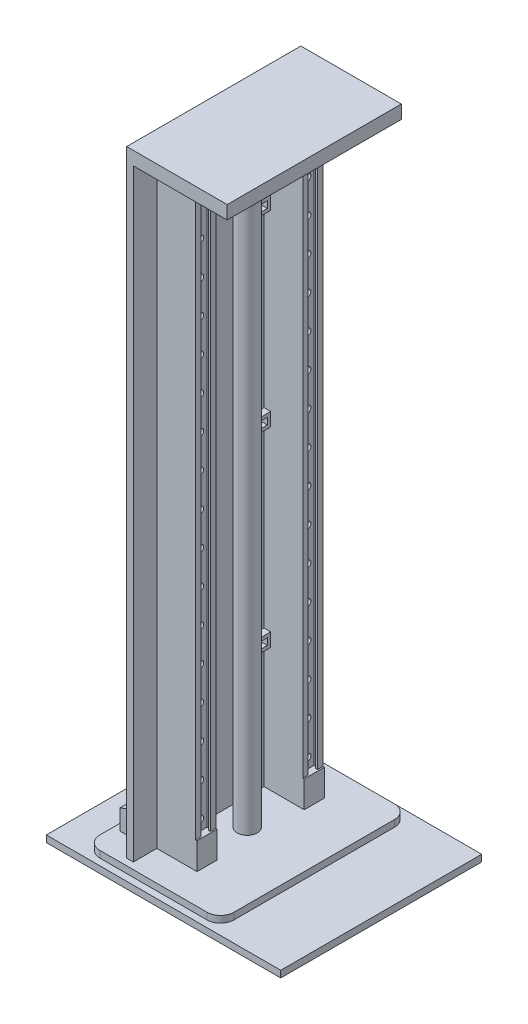
SolidWorks part; units mm, degrees
ref_plane "前视基准面" through (0, 0, 0) normal (0, 0, 1) x (1, 0, 0)
ref_plane "上视基准面" through (0, 0, 0) normal (0, 1, 0) x (1, 0, 0)
ref_plane "右视基准面" through (0, 0, 0) normal (1, 0, 0) x (0, 0, -1)
sketch "草图1" plane through (0, 0, 0) normal (0, 1, 0) x (1, 0, 0)
  line L1 (-150, 50) -> (-150, 150)
  line L2 (-150, 150) -> (200, 150)
  line L3 (200, 150) -> (200, -150)
  line L4 (200, -150) -> (-150, -150)
  line L5 (-150, -150) -> (-150, 50)
  dimension "D1" = 200
  dimension "D2" = 150
  dimension "D3" = 150
extrude "凸台-拉伸1" add sketch "草图1" along normal blind 10
sketch "草图2" plane through (0, 10, 0) normal (0, 1, 0) x (1, 0, 0)
  line L1 (-100, -20) -> (-100, 120)
  line L2 (-80, 140) -> (80, 140)
  line L3 (100, 120) -> (100, -120)
  line L4 (80, -140) -> (-80, -140)
  line L5 (-100, -120) -> (-100, -20)
  arc A0 (-100, -120) -> (-80, -140) centre (-80, -120) ccw
  arc A1 (100, -120) -> (80, -140) centre (80, -120) cw
  arc A2 (-80, 140) -> (-100, 120) centre (-80, 120) ccw
  arc A3 (100, 120) -> (80, 140) centre (80, 120) ccw
  dimension "D1" = 20
  dimension "D2" = 20
  dimension "D3" = 20
  dimension "D4" = 20
  dimension "D5" = 120
  dimension "D6" = 120
extrude "凸台-拉伸2" add sketch "草图2" along normal blind 10
sketch "草图3" plane through (0, 20, 0) normal (0, 1, 0) x (1, 0, 0)
  line L0 (-100, -120) -> (-100, -100) construction
  line L1 (-100, 120) -> (-100, -120) construction
  line L2 (-100, -100) -> (-50, -100) construction
  line L3 (-100, 120) -> (-100, 100) construction
  line L4 (-100, 100) -> (-50, 100) construction
  line L5 (-50, 100) -> (-50, -100)
  line L6 (-50, -100) -> (-50, -130)
  line L7 (-50, -130) -> (-40, -130)
  line L8 (-50, 100) -> (-50, 130)
  line L9 (-50, 130) -> (-40, 130)
  line L10 (-40, 130) -> (-40, -130)
extrude "凸台-拉伸3" add sketch "草图3" along normal blind 900
sketch "草图4" plane through (0, 20, 0) normal (0, 1, 0) x (1, 0, 0)
  line L0 (-50, -130) -> (-50, -100) construction
  line L1 (-50, 130) -> (-50, -130) construction
  line L2 (-50, -100) -> (-90, -100)
  line L3 (-90, -100) -> (-90, -85)
  line L4 (-50, 130) -> (-50, 100) construction
  line L5 (-50, 100) -> (-90, 100)
  line L6 (-90, 100) -> (-90, 85)
  line L7 (-90, 85) -> (-50, 85)
  line L8 (-50, 85) -> (-50, 100)
  line L9 (-90, -85) -> (-50, -85)
  line L10 (-50, -85) -> (-50, -100)
extrude "凸台-拉伸4" add sketch "草图4" along normal blind 45
sketch "草图5" plane through (0, 0, -100) normal (0, 0, -1) x (-1, 0, 0)
  line L0 (90, 65) -> (90, 50)
  line L1 (90, 65) -> (90, 20) construction
  line L2 (90, 50) -> (50, 65)
  line L3 (50, 65) -> (90, 65)
extrude "切除-拉伸1" cut sketch "草图5" against normal through all both and the other way through all
sketch "草图6" plane through (0, 920, 0) normal (0, 1, 0) x (1, 0, 0)
  line L0 (-50, 130) -> (100, 130)
  line L1 (-50, 130) -> (-50, -130)
  line L2 (-50, -130) -> (100, -130)
  line L3 (100, -130) -> (100, 130)
extrude "凸台-拉伸5" add sketch "草图6" along normal blind 20
sketch "草图7" plane through (-40, 0, 0) normal (1, 0, 0) x (0, 0, -1)
  line L0 (-130, 920) -> (-95, 920) construction
  line L1 (-130, 920) -> (130, 920) construction
  line L2 (-95, 920) -> (-65, 920)
  line L3 (-130, 920) -> (130, 920) construction
  line L4 (130, 920) -> (95, 920) construction
  line L5 (95, 920) -> (65, 920)
  line L6 (-95, 920) -> (-95, 60)
  line L7 (-65, 920) -> (-65, 60)
  line L9 (65, 920) -> (65, 60)
  line L11 (95, 60) -> (95, 920)
  line L12 (65, 60) -> (65, 20)
  line L13 (-130, 20) -> (130, 20) construction
  line L14 (65, 20) -> (95, 20)
  line L15 (95, 20) -> (95, 60)
  line L16 (-95, 60) -> (-95, 20)
  line L17 (-95, 20) -> (-65, 20)
  line L18 (-65, 20) -> (-65, 60)
  dimension "D1" = 35
extrude "凸台-拉伸6" add sketch "草图7" along normal blind 60
sketch "草图8" plane through (0, 20, 0) normal (0, 1, 0) x (1, 0, 0)
  circle A0 centre (0, 0) radius 15
extrude "凸台-拉伸7" add sketch "草图8" along normal up to next
sketch "草图11" plane through (0, 920, 0) normal (0, -1, 0) x (1, 0, 0)
  circle A0 centre (0, 0) radius 18
  circle A1 centre (0, 0) radius 24
extrude "凸台-拉伸10" add sketch "草图11" along normal blind 15
sketch "草图12" plane through (20, 0, 0) normal (1, 0, 0) x (0, 0, -1)
  line L0 (65, 920) -> (65, 60)
  line L1 (65, 920) -> (65, 20) construction
  line L2 (65, 60) -> (95, 60)
  line L3 (95, 20) -> (95, 920) construction
  line L4 (95, 60) -> (95, 920)
  line L5 (95, 920) -> (65, 920)
  line L6 (-95, 920) -> (-95, 60)
  line L7 (-95, 920) -> (-95, 20) construction
  line L8 (-95, 60) -> (-65, 60)
  line L9 (-65, 20) -> (-65, 920) construction
  line L10 (-65, 60) -> (-65, 920)
  line L11 (-65, 920) -> (-95, 920)
extrude "切除-拉伸3" cut sketch "草图12" against normal blind 10
sketch "草图13" plane through (10, 0, 0) normal (1, 0, 0) x (0, 0, -1)
  line L0 (-95, 60) -> (-90, 60)
  line L1 (-95, 60) -> (-65, 60) construction
  line L2 (-65, 60) -> (-70, 60)
  line L3 (-95, 60) -> (-95, 920)
  line L4 (-95, 920) -> (-90, 920)
  line L5 (-65, 920) -> (-95, 920) construction
  line L6 (-90, 920) -> (-90, 60)
  line L7 (-70, 60) -> (-70, 920)
  line L8 (-70, 920) -> (-65, 920)
  line L9 (-65, 60) -> (-65, 920) construction
  line L10 (-65, 920) -> (-65, 60)
  line L11 (65, 920) -> (70, 920)
  line L13 (95, 920) -> (65, 920) construction
  line L14 (95, 920) -> (90, 920)
  line L15 (65, 920) -> (65, 60)
  line L16 (65, 60) -> (70, 60)
  line L17 (65, 60) -> (95, 60) construction
  line L18 (70, 60) -> (70, 920)
  line L19 (95, 60) -> (95, 920)
  line L20 (90, 920) -> (90, 60)
  line L21 (90, 60) -> (95, 60)
extrude "凸台-拉伸11" add sketch "草图13" along normal blind 5
sketch "草图14" plane through (15, 0, 0) normal (1, 0, 0) x (0, 0, -1)
  line L0 (-95, 920) -> (-87, 920)
  line L1 (-87, 920) -> (-87, 60)
  line L2 (-87, 60) -> (-95, 60)
  line L3 (-95, 920) -> (-95, 60) construction
  line L4 (-95, 60) -> (-95, 920)
  line L5 (-65, 920) -> (-73, 920)
  line L6 (-73, 920) -> (-73, 60)
  line L7 (-73, 60) -> (-65, 60)
  line L8 (-65, 60) -> (-65, 920)
  line L9 (65, 920) -> (73, 920)
  line L10 (73, 920) -> (73, 60)
  line L11 (73, 60) -> (65, 60)
  line L12 (65, 60) -> (65, 920)
  line L13 (95, 920) -> (87, 920)
  line L14 (87, 920) -> (87, 60)
  line L15 (87, 60) -> (95, 60)
  line L16 (95, 60) -> (95, 920)
extrude "凸台-拉伸12" add sketch "草图14" along normal blind 3
sketch "草图17" plane through (10, 0, 0) normal (1, 0, 0) x (0, 0, -1)
  circle A0 centre (-80, 675) radius 5
  circle A1 centre (-80, 625) radius 5
  circle A2 centre (-80, 575) radius 5
  circle A3 centre (-80, 525) radius 5
  circle A4 centre (-80, 475) radius 5
  circle A5 centre (-80, 425) radius 5
  circle A6 centre (-80, 375) radius 5
  circle A7 centre (-80, 325) radius 5
  circle A8 centre (-80, 275) radius 5
  circle A9 centre (-80, 225) radius 5
  circle A10 centre (-80, 175) radius 5
  circle A11 centre (-80, 125) radius 5
  circle A12 centre (-80, 75) radius 5
  circle A13 centre (80, 675) radius 5
  circle A14 centre (80, 625) radius 5
  circle A15 centre (80, 575) radius 5
  circle A16 centre (80, 525) radius 5
  circle A17 centre (80, 475) radius 5
  circle A18 centre (80, 425) radius 5
  circle A19 centre (80, 375) radius 5
  circle A20 centre (80, 325) radius 5
  circle A21 centre (80, 275) radius 5
  circle A22 centre (80, 225) radius 5
  circle A23 centre (80, 175) radius 5
  circle A24 centre (80, 125) radius 5
  circle A25 centre (80, 75) radius 5
  circle A26 centre (-80, 725) radius 5
  circle A27 centre (-80, 775) radius 5
  circle A28 centre (-80, 825) radius 5
  circle A29 centre (-80, 875) radius 5
  circle A30 centre (80, 725) radius 5
  circle A31 centre (80, 775) radius 5
  circle A32 centre (80, 825) radius 5
  circle A33 centre (80, 875) radius 5
  dimension "D1" = 13
  dimension "D2" = 13
  dimension "D3" = 5
  dimension "D4" = 5
extrude "切除-拉伸4" cut sketch "草图17" against normal blind 5
sketch "草图20" plane through (-40, 0, 0) normal (1, 0, 0) x (0, 0, -1)
  line L0 (-45, 225) -> (-45, 205)
  line L2 (-45, 225) -> (-65, 225)
  line L4 (-65, 20) -> (-65, 920) construction
  line L5 (0, 180) -> (0, 92.1801) construction
  line L6 (-65, 225) -> (-65, 205)
  line L12 (45, 205) -> (45, 225)
  line L13 (45, 225) -> (65, 225)
  line L50 (-45, 490) -> (-45, 510)
  line L58 (-65, 490) -> (-45, 490)
  line L75 (-45, 510) -> (-65, 510)
  line L79 (-65, 510) -> (-65, 490)
  line L89 (-45, 205) -> (-65, 205)
  line L91 (-65, 790) -> (-65, 770)
  line L92 (-65, 790) -> (-45, 790)
  line L94 (-45, 770) -> (-65, 770)
  line L96 (65, 510) -> (65, 490)
  line L97 (45, 510) -> (65, 510)
  line L98 (45, 490) -> (45, 510)
  line L99 (65, 490) -> (45, 490)
  line L101 (65, 205) -> (65, 225)
  line L102 (45, 205) -> (65, 205)
  line L104 (-45, 770) -> (-45, 790)
  line L107 (45, 770) -> (65, 770)
  line L108 (65, 790) -> (65, 770)
  line L109 (65, 790) -> (45, 790)
  line L110 (45, 770) -> (45, 790)
extrude "凸台-拉伸13" add sketch "草图20" along normal blind 10
sketch "草图23" plane through (-30, 0, 0) normal (1, 0, 0) x (0, 0, -1)
  line L0 (-60, 785) -> (-50, 785)
  line L3 (-50, 785) -> (-50, 775)
  line L4 (-50, 775) -> (-60, 775)
  line L5 (-60, 775) -> (-60, 785)
  line L7 (-60, 505) -> (-50, 505)
  line L9 (-60, 220) -> (-50, 220)
  line L10 (-50, 505) -> (-50, 495)
  line L11 (-50, 495) -> (-60, 495)
  line L12 (-60, 495) -> (-60, 505)
  line L15 (-60, 220) -> (-60, 210)
  line L16 (-60, 210) -> (-50, 210)
  line L17 (-50, 210) -> (-50, 220)
  line L19 (0, 0) -> (0, 98.1056) construction
  line L20 (60, 220) -> (60, 210)
  line L21 (60, 210) -> (50, 210)
  line L22 (50, 210) -> (50, 220)
  line L23 (60, 220) -> (50, 220)
  line L24 (60, 495) -> (60, 505)
  line L25 (50, 495) -> (60, 495)
  line L26 (50, 505) -> (50, 495)
  line L27 (60, 505) -> (50, 505)
  line L28 (60, 775) -> (60, 785)
  line L29 (50, 775) -> (60, 775)
  line L30 (50, 785) -> (50, 775)
  line L31 (60, 785) -> (50, 785)
extrude "切除-拉伸8" cut sketch "草图23" against normal blind 20
